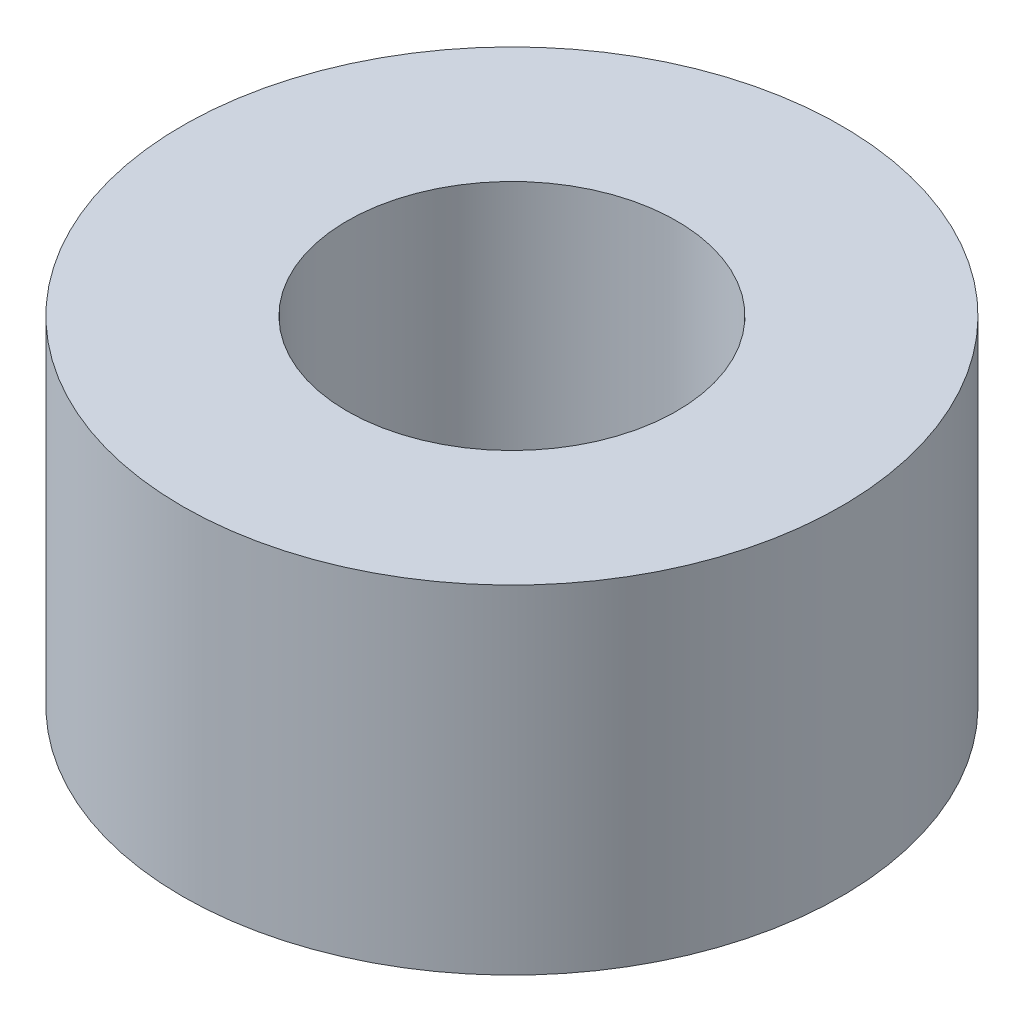
SolidWorks part; units mm, degrees
ref_plane "Ebene vorne" through (0, 0, 0) normal (0, 0, 1) x (1, 0, 0)
ref_plane "Ebene oben" through (0, 0, 0) normal (0, 1, 0) x (1, 0, 0)
ref_plane "Ebene rechts" through (0, 0, 0) normal (1, 0, 0) x (0, 0, -1)
sketch "Skizze1" plane through (0, 0, 0) normal (0, 1, 0) x (1, 0, 0)
  circle A0 centre (0, 0) radius 4
  dimension "D1" = 8
extrude "Aufsatz-Linear austragen1" add sketch "Skizze1" against normal blind 4.1
sketch "Skizze2" plane through (0, 0, 0) normal (0, 1, 0) x (1, 0, 0)
  circle A0 centre (0, 0) radius 2
extrude "Schnitt-Linear austragen1" cut sketch "Skizze2" against normal blind 4.1
